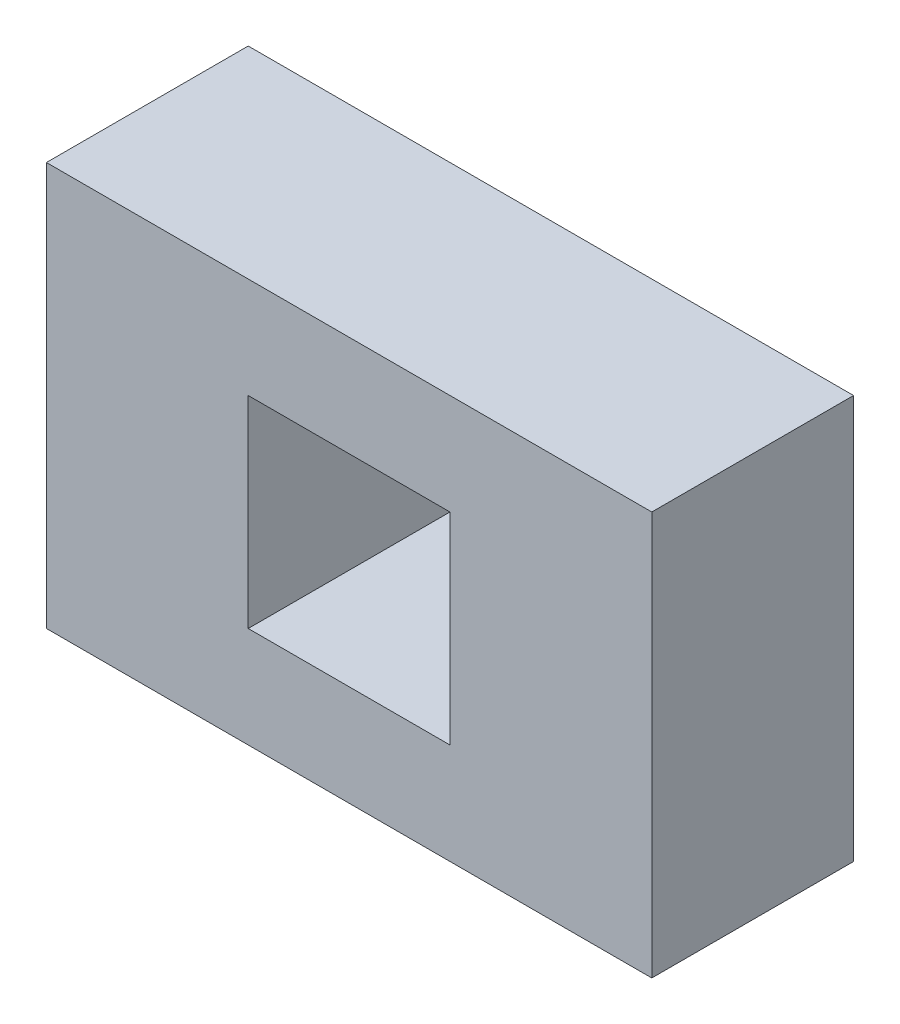
SolidWorks part; units mm, degrees
ref_plane "Plan de face" through (0, 0, 0) normal (0, 0, 1) x (1, 0, 0)
ref_plane "Plan de dessus" through (0, 0, 0) normal (0, 1, 0) x (1, 0, 0)
ref_plane "Plan de droite" through (0, 0, 0) normal (1, 0, 0) x (0, 0, -1)
sketch "Esquisse1" plane through (0, 0, 0) normal (0, 0, 1) x (1, 0, 0)
  line L1 (0, 0) -> (15, 0)
  line L2 (0, 0) -> (0, 10)
  line L3 (0, 10) -> (15, 10)
  line L4 (15, 0) -> (15, 10)
  line L5 (5, 7.5) -> (10, 7.5)
  line L6 (5, 7.5) -> (5, 2.5)
  line L7 (5, 2.5) -> (10, 2.5)
  line L8 (10, 7.5) -> (10, 2.5)
  dimension "D1" = 10
  dimension "D2" = 15
  dimension "D3" = 5
  dimension "D4" = 5
  dimension "D5" = 5
  dimension "D6" = 2.5
extrude "Boss.-Extru.1" add sketch "Esquisse1" along normal blind 5
